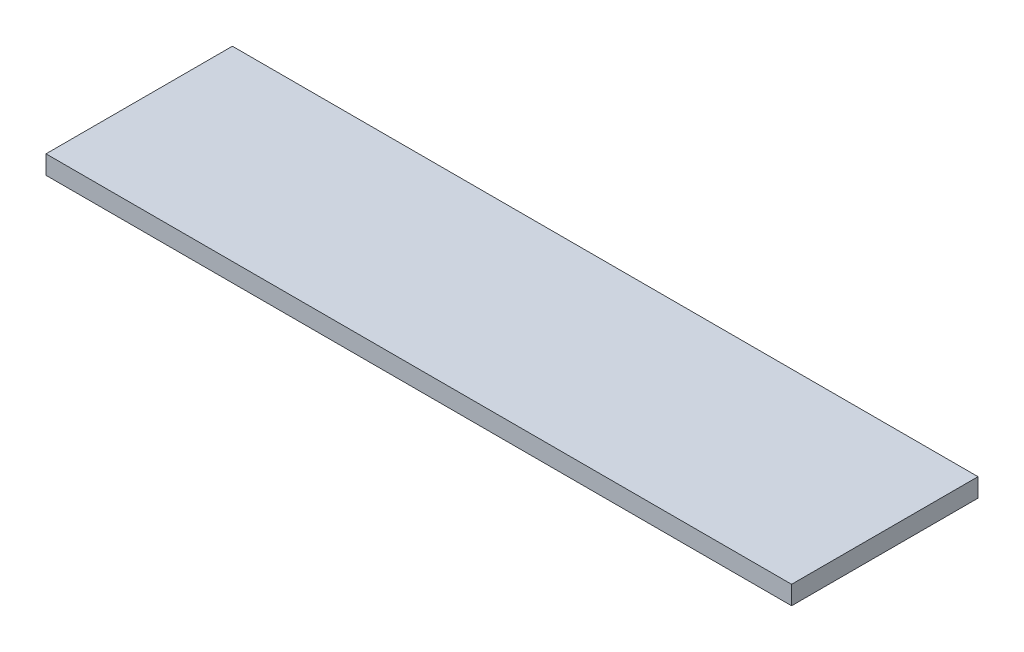
SolidWorks part; units mm, degrees
material "Acrylic (Medium-high impact)"
ref_plane "Front Plane" through (0, 0, 0) normal (0, 0, 1) x (1, 0, 0)
ref_plane "Top Plane" through (0, 0, 0) normal (0, 1, 0) x (1, 0, 0)
ref_plane "Right Plane" through (0, 0, 0) normal (1, 0, 0) x (0, 0, -1)
sketch "Sketch1" plane through (0, 0, 0) normal (0, 1, 0) x (1, 0, 0)
  line L1 (60, -15) -> (-60, -15)
  line L2 (60, -15) -> (60, 15)
  line L3 (60, 15) -> (-60, 15)
  line L4 (-60, -15) -> (-60, 15)
  line L5 (60, -15) -> (-60, 15) construction
  line L6 (60, 15) -> (-60, -15) construction
  point P0 (0, 0)
  dimension "D1" = 30
  dimension "D2" = 120
extrude "Boss-Extrude1" add sketch "Sketch1" along normal blind 3
equation "\"L\" = 120"
equation "\"D2@Sketch1\"=\"L\""
